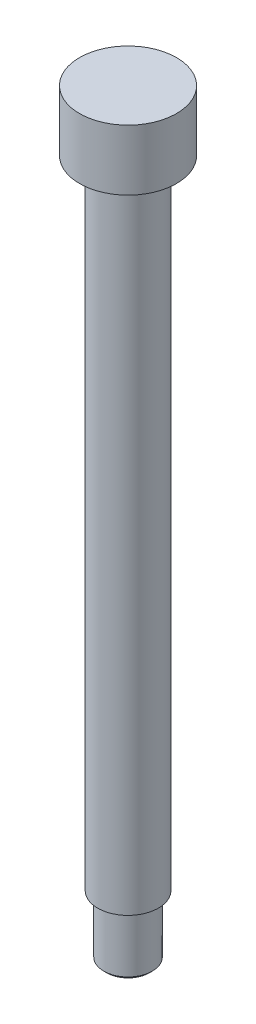
SolidWorks part; units mm, degrees
material "Plain Carbon Steel"
ref_plane "Front Plane" through (0, 0, 0) normal (0, 0, 1) x (1, 0, 0)
ref_plane "Top Plane" through (0, 0, 0) normal (0, 1, 0) x (1, 0, 0)
ref_plane "Right Plane" through (0, 0, 0) normal (1, 0, 0) x (0, 0, -1)
sketch "Sketch1" plane through (0, 0, 0) normal (0, 0, 1) x (1, 0, 0)
  line L0 (0, 0) -> (8, 0)
  line L1 (5, -10) -> (5, -115)
  line L2 (5, -115) -> (4, -115)
  line L3 (4, -115) -> (4, -125)
  line L4 (4, -125) -> (0, -125)
  line L5 (0, -125) -> (0, 0)
  line L6 (0, -130) -> (0, 5) construction
  line L7 (5, -10) -> (8, -10)
  line L8 (8, -10) -> (8, 0)
  dimension "D1" = 5
  dimension "D2" = 5
  dimension "D3" = 8
  dimension "D4" = 10
  dimension "D5" = 16
  dimension "D6" = 10
  dimension "D7" = 125
  dimension "D8" = 10
revolve "Revolve1" add sketch "Sketch1" angle 360 about L6
cosmetic thread "Cosmetic Thread1" parameters "D1"=10, "D2"=6.619
chamfer "Chamfer1" distance 0.5 angle 45 1 edges at (0, -125, -4)
